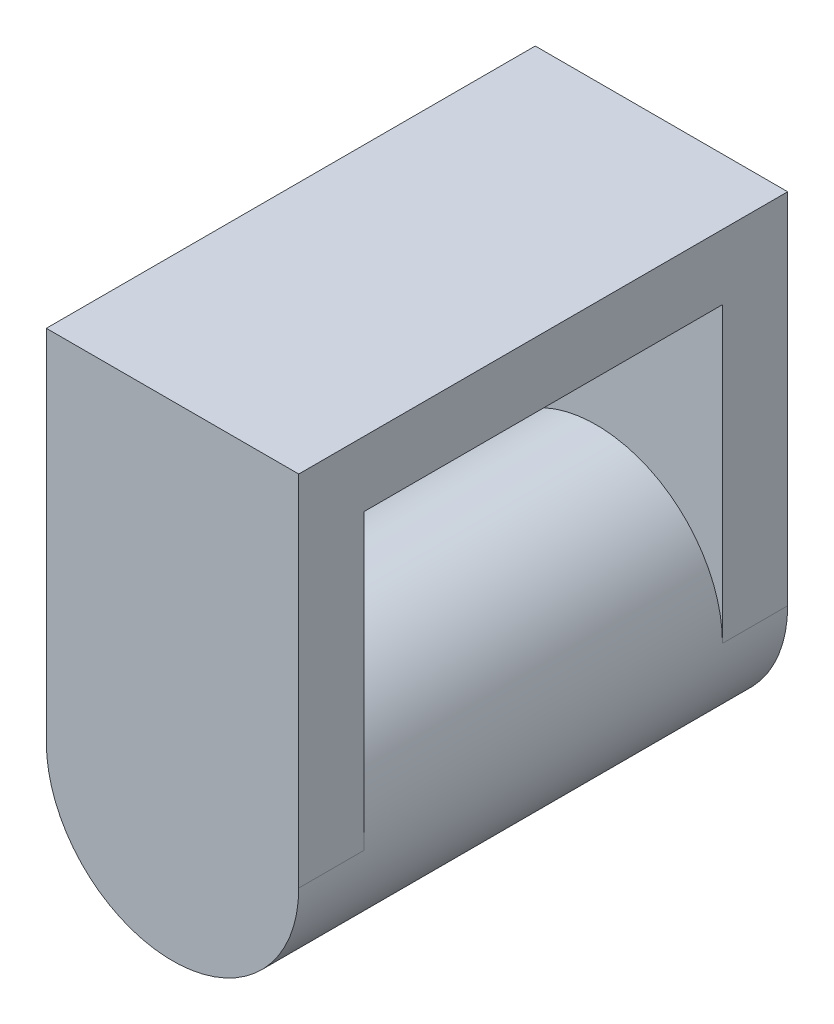
SolidWorks part; units mm, degrees
ref_plane "Front Plane" through (0, 0, 0) normal (0, 0, 1) x (1, 0, 0)
ref_plane "Top Plane" through (0, 0, 0) normal (0, 1, 0) x (1, 0, 0)
ref_plane "Right Plane" through (0, 0, 0) normal (1, 0, 0) x (0, 0, -1)
sketch "Sketch1" plane through (0, 0, 0) normal (0, 0, 1) x (1, 0, 0)
  line L0 (6.1468, 0) -> (6.1468, 14.2875) construction
  line L1 (-6.1468, 17.4625) -> (6.1468, 17.4625)
  line L2 (-6.1468, 17.4625) -> (-6.1468, 14.2875)
  line L3 (-6.1468, 14.2875) -> (6.1468, 14.2875)
  line L4 (6.1468, 17.4625) -> (6.1468, 14.2875)
  line L5 (-6.1468, 17.4625) -> (6.1468, 14.2875) construction
  line L6 (-6.1468, 14.2875) -> (6.1468, 17.4625) construction
  circle A0 centre (0, 0) radius 6.1468
  point P3 (0, 15.875)
  dimension "D1" = 12.2936
  dimension "D3" = 14.2875
  dimension "D4" = 3.175
extrude "Boss-Extrude1" add sketch "Sketch1" along normal mid plane 17.4625
sketch "Sketch2" plane through (0, 0, 8.7312) normal (0, 0, 1) x (1, 0, 0)
  line L0 (-6.1468, 0) -> (-6.1468, 17.4625)
  line L1 (-6.1468, 17.4625) -> (6.1468, 17.4625)
  line L2 (6.1468, 17.4625) -> (6.1468, 0)
  arc A1 (6.1468, 0) -> (-6.1468, 0) centre (0, 0) cw
extrude "Boss-Extrude2" add sketch "Sketch2" along normal blind 3.175
mirror "Mirror1" about plane through (0, 0, 0) normal (0, 0, 1) of "Boss-Extrude2"
